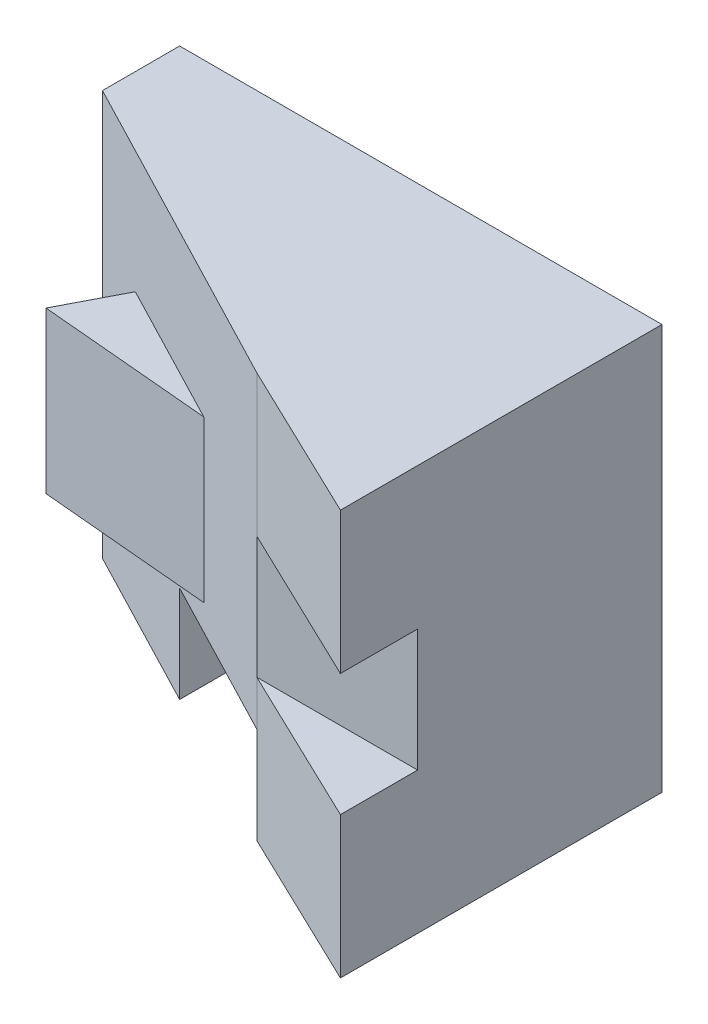
SolidWorks part; units mm, degrees
ref_plane "Front Plane" through (0, 0, 0) normal (0, 0, 1) x (1, 0, 0)
ref_plane "Top Plane" through (0, 0, 0) normal (0, 1, 0) x (1, 0, 0)
ref_plane "Right Plane" through (0, 0, 0) normal (1, 0, 0) x (0, 0, -1)
sketch "Sketch1" plane through (0, 0, 0) normal (0, 0, 1) x (1, 0, 0)
  line L1 (0, 0) -> (75, 0)
  line L2 (0, 0) -> (0, -63)
  line L3 (0, -63) -> (75, -63)
  line L4 (75, 0) -> (75, -63)
  dimension "D1" = 63
  dimension "D2" = 75
extrude "Boss-Extrude1" add sketch "Sketch1" along normal blind 12 from offset 0 contours L2 L1 L4 L3
sketch "Sketch2" plane through (0, -63, 0) normal (0, -1, 0) x (-1, 0, 0)
  line L6 (0, 0) -> (-25, 0)
  line L7 (0, 0) -> (0, -25)
  line L8 (0, -25) -> (-25, -25)
  line L9 (-25, 0) -> (-25, -25)
  dimension "D1" = 25
  dimension "D2" = 25
extrude "Boss-Extrude2" add sketch "Sketch2" against normal blind 63
sketch "Sketch3" plane through (0, -63, 0) normal (0, -1, 0) x (-1, 0, 0)
  line L0 (-25, -25) -> (0, -12)
  line L1 (0, -25) -> (0, 0) construction
  line L2 (0, -12) -> (0, -25)
  line L3 (-25, -25) -> (0, -25) construction
  line L4 (0, -25) -> (-25, -25)
  dimension "D1" = 12
extrude "Cut-Extrude1" cut sketch "Sketch3" against normal blind 114
sketch "Sketch4" plane through (0, -63, 0) normal (0, -1, 0) x (1, 0, 0)
  line L5 (75, 50) -> (50, 38)
  line L6 (75, 0) -> (50, 0)
  line L7 (75, 0) -> (75, 50)
  line L9 (50, 0) -> (50, 38)
  dimension "D1" = 50
extrude "Boss-Extrude3" add sketch "Sketch4" against normal blind 63
sketch "Sketch6" plane through (0, -63, 0) normal (0, -1, 0) x (1, 0, 0)
  line L0 (0, 0) -> (75, 0) construction
  line L1 (25, 12) -> (50, 12)
  line L2 (25, 12) -> (25, 0)
  line L3 (25, 0) -> (50, 0)
  line L4 (50, 12) -> (50, 0)
  dimension "D1" = 25
extrude "Cut-Extrude2" cut sketch "Sketch6" against normal blind 15
sketch "Sketch7" plane through (0, -48, 0) normal (0, -1, 0) x (1, 0, 0)
  line L0 (50, 38) -> (50, 12)
  line L1 (50, 12) -> (25, 12)
  line L2 (25, 12) -> (25, 25)
  line L3 (25, 0) -> (25, 25) construction
  line L4 (25, 25) -> (50, 38)
extrude "Boss-Extrude5" add sketch "Sketch7" against normal blind 48
sketch "Sketch8" plane through (75, 0, 0) normal (1, 0, 0) x (0, 0, -1)
  line L0 (-50, -63) -> (-50, 0) construction
  line L1 (-50, 0) -> (0, 0) construction
  line L2 (-50, -41) -> (-38, -41)
  line L3 (-50, -41) -> (-50, -22)
  line L4 (-50, -22) -> (-38, -22)
  line L5 (-38, -41) -> (-38, -22)
  line L6 (-50, -63) -> (0, -63) construction
  dimension "D1" = 22
  dimension "D2" = 22
  dimension "D3" = 12
extrude "Cut-Extrude3" cut sketch "Sketch8" against normal blind 25
sketch "Sketch9" plane through (-4.9118, 0, 9.4458) normal (-0.4614, 0, 0.8872) x (0.8872, 0, 0.4614)
  line L1 (17.5362, -19) -> (42.5362, -19)
  line L2 (17.5362, -19) -> (17.5362, -44)
  line L3 (17.5362, -44) -> (42.5362, -44)
  line L4 (42.5362, -19) -> (42.5362, -44)
  line L5 (61.8922, 0) -> (5.5362, 0) construction
  line L6 (42.5362, -44) -> (62.3635, -44) construction
  line L7 (5.5362, 0) -> (5.5362, -63) construction
  dimension "D1" = 25
  dimension "D2" = 25
  dimension "D3" = 19
  dimension "D4" = 12
extrude "Boss-Extrude7" add sketch "Sketch9" along normal blind 44
sketch "Sketch12" plane through (0, -44, 0) normal (0, -1, 0) x (-1, 0, 0)
  line L1 (9.6529, -56.5738) -> (-10.6466, -17.5362) construction
  line L2 (-3.265, -31.7317) -> (9.6529, -56.5738)
  line L3 (9.6529, -56.5738) -> (-12.5275, -68.1076)
  line L4 (-12.5275, -68.1076) -> (-32.827, -29.0701)
  line L5 (-12.5275, -68.1076) -> (-32.827, -29.0701) construction
  line L6 (-3.265, -31.7317) -> (-32.827, -29.0701)
  dimension "D1" = 16
extrude "Cut-Extrude7" cut sketch "Sketch12" against normal blind 44
sketch "Sketch13" plane through (0, -44, 0) normal (0, -1, 0) x (1, 0, 0)
  line L0 (32.827, 29.0701) -> (5.8962, 26.6716)
  line L1 (3.265, 31.7317) -> (10.6466, 17.5362) construction
  line L2 (5.8962, 26.6716) -> (3.265, 31.7317)
  line L3 (3.265, 31.7317) -> (32.827, 29.0701)
extrude "Cut-Extrude8" cut sketch "Sketch13" against normal blind 44
